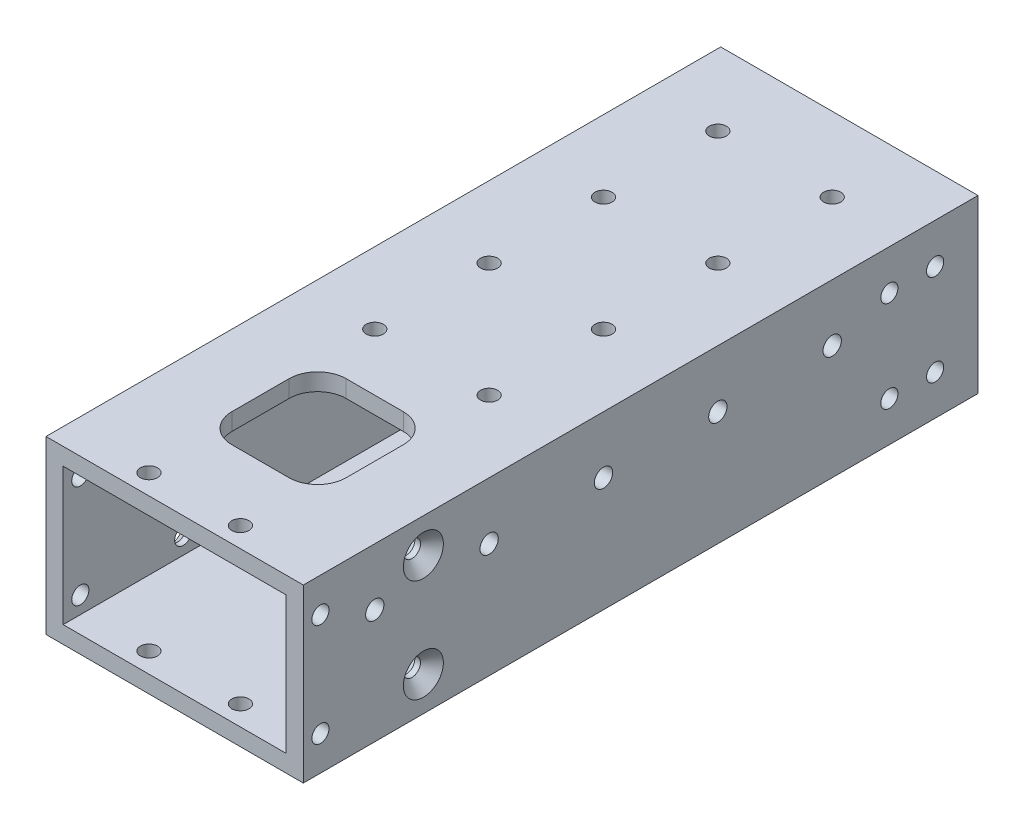
SolidWorks part; units mm, degrees
material "Thornel Mat VMA"
ref_plane "前视基准面" through (0, 0, 0) normal (0, 0, 1) x (1, 0, 0)
ref_plane "上视基准面" through (0, 0, 0) normal (0, 1, 0) x (1, 0, 0)
ref_plane "右视基准面" through (0, 0, 0) normal (1, 0, 0) x (0, 0, -1)
other "Configuration Table"
sketch "草图1" plane through (0, 0, 0) normal (0, 0, 1) x (1, 0, 0)
  line L1 (-22.5, -15) -> (22.5, -15)
  line L2 (-22.5, -15) -> (-22.5, 15)
  line L3 (-22.5, 15) -> (22.5, 15)
  line L4 (22.5, -15) -> (22.5, 15)
  line L5 (-22.5, -15) -> (22.5, 15) construction
  line L6 (-22.5, 15) -> (22.5, -15) construction
  point P0 (0, 0)
  dimension "D1" = 45
  dimension "D2" = 30
extrude "拉伸-薄壁1" add sketch "草图1" along normal blind 118 thin thin type one direction reverse wall 3
sketch "草图2" plane through (-22.5, 0, 0) normal (-1, 0, 0) x (0, 0, 1)
  line L0 (0, 0) -> (11.5, 0) construction
  line L1 (11.5, 0) -> (106, 0) construction
  line L2 (118, 15) -> (118, -15) construction
  line L3 (97, -9) -> (115, -9) construction
  line L4 (97, -9) -> (97, 9) construction
  line L5 (97, 9) -> (115, 9) construction
  line L6 (115, -9) -> (115, 9) construction
  line L7 (97, -9) -> (115, 9) construction
  line L8 (97, 9) -> (115, -9) construction
  line L9 (7.5, -8) -> (15.5, -8) construction
  line L10 (7.5, -8) -> (7.5, 8) construction
  line L11 (7.5, 8) -> (15.5, 8) construction
  line L12 (15.5, -8) -> (15.5, 8) construction
  line L13 (7.5, -8) -> (15.5, 8) construction
  line L14 (7.5, 8) -> (15.5, -8) construction
  line L15 (0, 15) -> (0, -15) construction
  circle A0 centre (15.5, 8) radius 1.5
  circle A1 centre (15.5, -8) radius 1.5
  circle A2 centre (7.5, -8) radius 1.5
  circle A3 centre (7.5, 8) radius 1.5
  circle A4 centre (115, 9) radius 1.5
  circle A5 centre (97, 9) radius 1.5
  circle A6 centre (97, -9) radius 1.5
  circle A7 centre (115, -9) radius 1.5
  dimension "D5" = 3
  dimension "D1" = 8
  dimension "D2" = 18
  dimension "D3" = 12
  dimension "D4" = 11.5
  dimension "D6" = 16
extrude "切除-拉伸1" cut sketch "草图2" against normal blind 59
sketch "草图3" plane through (0, -12, 0) normal (0, 1, 0) x (1, 0, 0)
  line L0 (0, 0) -> (0, -13) construction
  line L1 (22.5, 0) -> (-22.5, 0) construction
  line L2 (22.5, -118) -> (22.5, 0) construction
  line L3 (-15.5, -26) -> (15.5, -26)
  line L4 (-15.5, -26) -> (-15.5, 0)
  line L5 (-15.5, 0) -> (15.5, 0)
  line L6 (15.5, -26) -> (15.5, 0)
  line L7 (-15.5, -26) -> (15.5, 0) construction
  line L8 (-15.5, 0) -> (15.5, -26) construction
  dimension "D1" = 7
  dimension "D2" = 26
extrude "切除-拉伸2" cut sketch "草图3" against normal blind 10
sketch "草图4" plane through (22.5, 0, 0) normal (1, 0, 0) x (0, 0, -1)
  line L0 (0, 5) -> (-25.5, 5) construction
  line L1 (-118, -15) -> (0, -15) construction
  line L2 (0, -15) -> (0, 15) construction
  circle A0 centre (-25.5, 5) radius 1.6
  circle A1 centre (-45.5, 5) radius 1.6
  circle A2 centre (-65.5, 5) radius 1.6
  circle A3 centre (-85.5, 5) radius 1.6
  circle A4 centre (-105.5, 5) radius 1.6
  dimension "D1" = 3.2
  dimension "D3" = 20
  dimension "D4" = 25.5
  dimension "D5" = 20
  dimension "D2" = 5
extrude "切除-拉伸3" cut sketch "草图4" against normal blind 50
chamfer "倒角1" distance 2 angle 45 4 edges at (-22.5, -9, 98.5) (-22.5, 9, 98.5) (22.5, -9, 98.5) (22.5, 9, 98.5)
fillet "圆角1" radius 2 4 edges at (-15.5, -13.5, 0) (-15.5, -13.5, 26) (15.5, -13.5, 26) (15.5, -13.5, 0)
sketch "草图5" plane through (0, 15, 0) normal (0, 1, 0) x (1, 0, 0)
  line L0 (0, -93) -> (0, -6.1822) construction
  line L1 (-10, -103) -> (10, -103)
  line L2 (-10, -103) -> (-10, -83)
  line L3 (-10, -83) -> (10, -83)
  line L4 (10, -103) -> (10, -83)
  line L5 (-10, -103) -> (10, -83) construction
  line L6 (-10, -83) -> (10, -103) construction
  line L7 (22.5, -118) -> (-22.5, -118) construction
  line L9 (5, -68) -> (-5, -68) construction
  line L10 (5, -68) -> (5, -58) construction
  line L11 (5, -58) -> (-5, -58) construction
  line L12 (-5, -68) -> (-5, -58) construction
  line L13 (5, -68) -> (-5, -58) construction
  line L14 (5, -58) -> (-5, -68) construction
  point P0 (0, -93)
  point P10 (0, -63)
  dimension "D1" = 20
  dimension "D2" = 20
  dimension "D3" = 15
  dimension "D4" = 10
  dimension "D5" = 10
  dimension "D6" = 30
extrude "切除-拉伸4" cut sketch "草图5" against normal blind 3
sketch "草图6" plane through (0, 15, 0) normal (0, 1, 0) x (1, 0, 0)
  line L0 (-10, -73) -> (10, -73) construction
  line L1 (0, -73) -> (0, 0) construction
  line L2 (10, -83) -> (-10, -83) construction
  circle A0 centre (10, -73) radius 1.5
  circle A1 centre (-10, -73) radius 1.5
  circle A2 centre (-10, -53) radius 1.5
  circle A3 centre (10, -53) radius 1.5
  circle A4 centre (-10, -33) radius 1.5
  circle A5 centre (10, -33) radius 1.5
  circle A6 centre (-10, -13) radius 1.5
  circle A7 centre (10, -13) radius 1.5
  dimension "D3" = 3
  dimension "D5" = 20
  dimension "D1" = 20
  dimension "D2" = 10
  dimension "D4" = 4
extrude "切除-拉伸5" cut sketch "草图6" against normal blind 42
fillet "圆角2" radius 5 4 edges at (10, 13.5, 103) (-10, 13.5, 103) (10, 13.5, 83) (-10, 13.5, 83)
sketch "草图7" plane through (0, 15, 0) normal (0, 1, 0) x (1, 0, 0)
  line L0 (-8, -114.5) -> (8, -114.5) construction
  line L1 (0, -114.5) -> (0, -118) construction
  line L2 (22.5, -118) -> (-22.5, -118) construction
  circle A0 centre (8, -114.5) radius 1.5
  circle A1 centre (-8, -114.5) radius 1.5
  dimension "D3" = 3
  dimension "D1" = 3.5
  dimension "D2" = 16
  dimension "D4" = 8
extrude "切除-拉伸6" cut sketch "草图7" against normal blind 30
